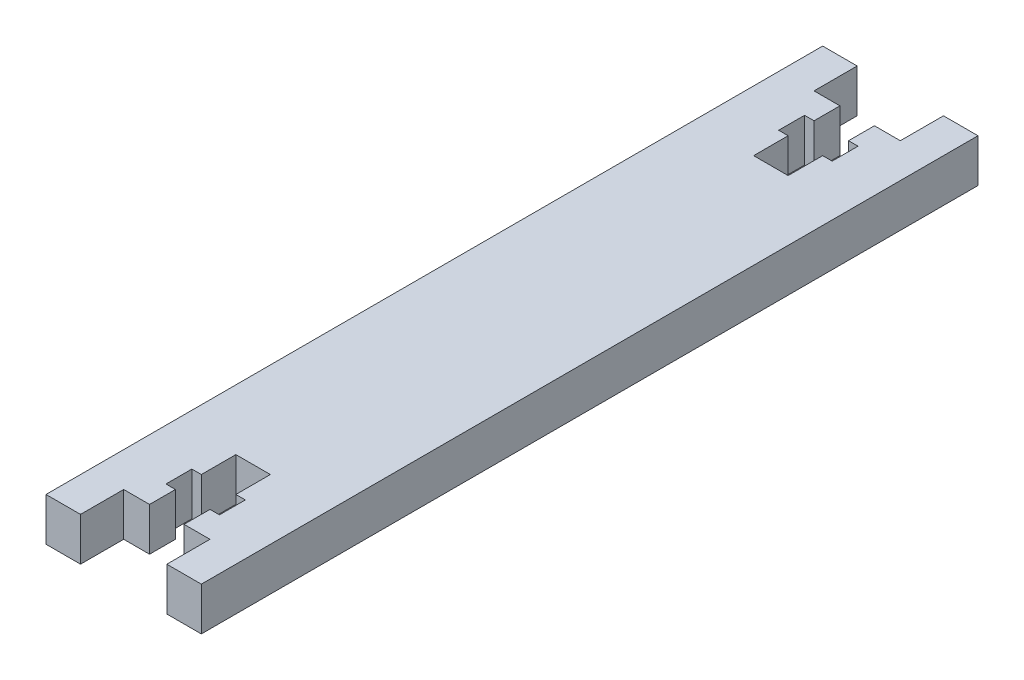
SolidWorks part; units mm, degrees
ref_plane "Front Plane" through (0, 0, 0) normal (0, 0, 1) x (1, 0, 0)
ref_plane "Top Plane" through (0, 0, 0) normal (0, 1, 0) x (1, 0, 0)
ref_plane "Right Plane" through (0, 0, 0) normal (1, 0, 0) x (0, 0, -1)
sketch "Sketch1" plane through (0, 0, 0) normal (0, 1, 0) x (1, 0, 0)
  line L0 (-3.6453, 61.367) -> (-3.6453, -18.633) construction
  line L1 (-8.6453, 61.367) -> (-5.6453, 61.367)
  line L2 (-12.6453, 61.367) -> (-12.6453, 16.367)
  line L3 (-8.6453, -18.633) -> (-5.6453, -18.633)
  line L4 (5.3547, 61.367) -> (5.3547, 16.367)
  line L5 (-12.6453, -23.633) -> (-8.6453, -23.633)
  line L7 (5.3547, -18.633) -> (5.3547, -23.633)
  line L8 (5.3547, -23.633) -> (1.3547, -23.633)
  line L9 (1.3547, -18.633) -> (1.3547, -23.633)
  line L10 (-8.6453, -18.633) -> (-8.6453, -23.633)
  line L11 (-12.6453, -18.633) -> (-12.6453, -23.633)
  line L21 (5.3547, -3.633) -> (5.3547, -18.633)
  line L22 (-12.6453, 16.367) -> (-12.6453, -3.633)
  line L37 (5.3547, -3.633) -> (5.3547, 16.367)
  line L48 (5.3547, 16.367) -> (5.3547, 31.367)
  line L56 (5.3547, -48.633) -> (5.3547, -3.633)
  line L58 (-12.6453, -48.633) -> (-12.6453, -3.633)
  line L66 (-12.6453, 16.367) -> (-12.6453, 31.367)
  line L90 (-12.6453, -3.633) -> (-12.6453, -18.633)
  line L98 (-12.6453, 61.367) -> (-12.6453, 16.367)
  line L101 (-12.6453, -3.633) -> (-12.6453, -18.633)
  line L102 (-1.6453, -18.633) -> (1.3547, -18.633)
  line L106 (-5.6453, -18.633) -> (-5.6453, -15.633)
  line L107 (-5.6453, -12.633) -> (-6.7453, -12.633)
  line L109 (-5.6453, -15.633) -> (-6.7453, -15.633)
  line L110 (-6.7453, -12.633) -> (-6.7453, -15.633)
  line L111 (-5.6453, -12.633) -> (-5.6453, -8.633)
  line L112 (-1.6453, -15.633) -> (-0.5453, -15.633)
  line L113 (-5.6453, -8.633) -> (-1.6453, -8.633)
  line L114 (-5.6453, -8.633) -> (-5.6453, -12.633)
  line L117 (-1.6453, -12.633) -> (-0.5453, -12.633)
  line L118 (-0.5453, -12.633) -> (-0.5453, -15.633)
  line L119 (-1.6453, -18.633) -> (-1.6453, -15.633)
  line L120 (-1.6453, -12.633) -> (-1.6453, -8.633)
  line L121 (-5.6453, -15.633) -> (-5.6453, -18.633)
  line L122 (-3.6453, 21.367) -> (23.4497, 21.367) construction
  line L123 (-5.6453, 58.367) -> (-5.6453, 61.367)
  line L124 (-1.6453, 55.367) -> (-1.6453, 51.367)
  line L125 (-1.6453, 61.367) -> (-1.6453, 58.367)
  line L126 (-0.5453, 55.367) -> (-0.5453, 58.367)
  line L127 (-1.6453, 55.367) -> (-0.5453, 55.367)
  line L128 (-5.6453, 51.367) -> (-5.6453, 55.367)
  line L129 (-5.6453, 51.367) -> (-1.6453, 51.367)
  line L130 (-1.6453, 58.367) -> (-0.5453, 58.367)
  line L131 (-5.6453, 55.367) -> (-5.6453, 51.367)
  line L132 (-6.7453, 55.367) -> (-6.7453, 58.367)
  line L133 (-5.6453, 58.367) -> (-6.7453, 58.367)
  line L134 (-5.6453, 55.367) -> (-6.7453, 55.367)
  line L135 (-5.6453, 61.367) -> (-5.6453, 58.367)
  line L136 (-1.6453, 61.367) -> (1.3547, 61.367)
  line L137 (-12.6453, 61.367) -> (-12.6453, 66.367)
  line L138 (-8.6453, 61.367) -> (-8.6453, 66.367)
  line L139 (1.3547, 61.367) -> (1.3547, 66.367)
  line L140 (5.3547, 66.367) -> (1.3547, 66.367)
  line L141 (5.3547, 61.367) -> (5.3547, 66.367)
  line L142 (-12.6453, 66.367) -> (-8.6453, 66.367)
  line L143 (-8.6453, 61.367) -> (-5.6453, 61.367)
  line L144 (-1.6453, 61.367) -> (1.3547, 61.367)
  dimension "D1" = 18
  dimension "D2" = 80
  dimension "D3" = 5
  dimension "D4" = 5
  dimension "D5" = 3
  dimension "D6" = 3
  dimension "D7" = 4
  dimension "D8" = 4
extrude "Boss-Extrude2" add sketch "Sketch1" along normal blind 5 contours L142 L137 L2 L22 L58 L11 L5 L10 L3 L106 L109 L110 L107 L111 L113 L120 L117 L118 L112 L119 L102 L9 L8 L7 L21 L37 L4 L141 L140 L139 L136 L125 L130 L126 L127 L124 L129 L128 L134 L132 L133 L123 L1 L138
